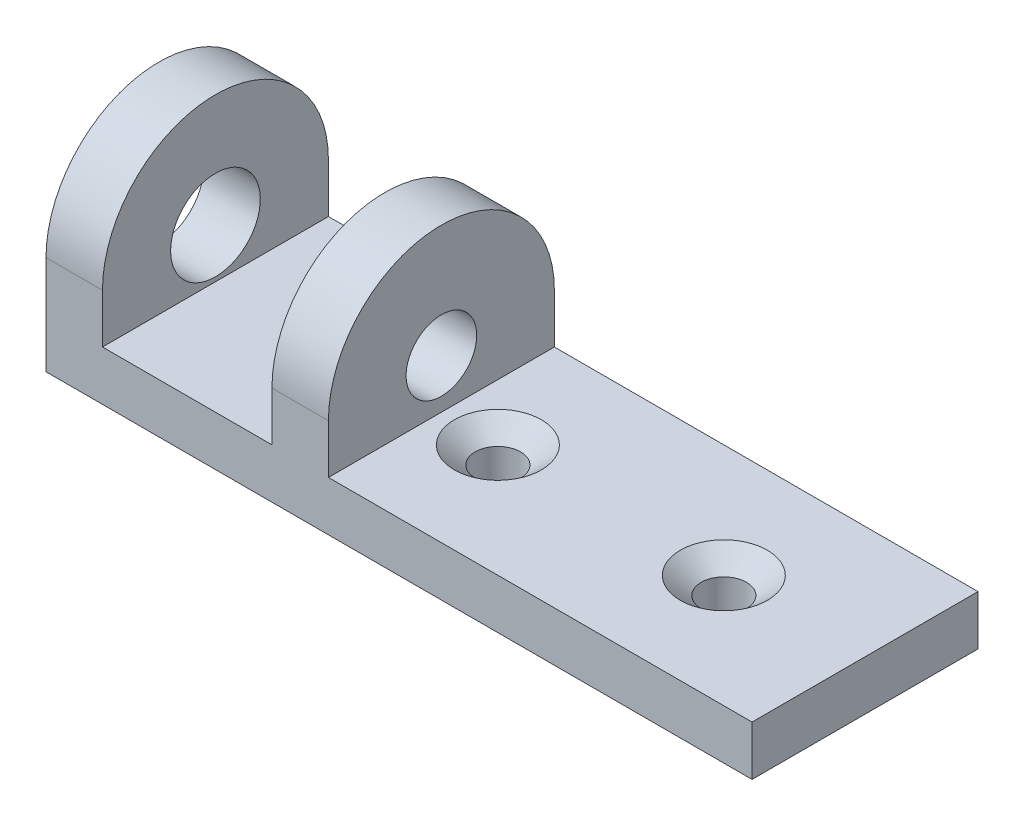
SolidWorks part; units mm, degrees
material "6061 Alloy"
ref_plane "Front" through (0, 0, 0) normal (0, 0, 1) x (1, 0, 0)
ref_plane "Top" through (0, 0, 0) normal (0, 1, 0) x (1, 0, 0)
ref_plane "Right" through (0, 0, 0) normal (1, 0, 0) x (0, 0, -1)
sketch "Sketch1" plane through (0, 0, 0) normal (1, 0, 0) x (0, 0, -1)
  line L0 (-12.7, 0) -> (-12.7, -11.1125)
  line L1 (-12.7, -11.1125) -> (12.7, -11.1125)
  line L2 (12.7, -11.1125) -> (12.7, 0)
  circle A0 centre (0, 0) radius 1.5875
  arc A1 (-12.7, 0) -> (12.7, 0) centre (0, 0) cw
  dimension "D1" = 3.175
  dimension "D2" = 25.4
  dimension "D3" = 11.1125
extrude "Boss-Extrude1" add sketch "Sketch1" along normal blind 79.375
sketch "Sketch2" plane through (0, 0, 12.7) normal (0, 0, 1) x (1, 0, 0)
  line L0 (79.375, 12.7) -> (0, 12.7) construction
  line L1 (6.35, 12.7) -> (25.4, 12.7)
  line L2 (6.35, 12.7) -> (6.35, -5.5245)
  line L3 (6.35, -5.5245) -> (25.4, -5.5245)
  line L4 (25.4, 12.7) -> (25.4, -5.5245)
  line L5 (79.375, 0) -> (79.375, -11.1125) construction
  line L6 (31.75, 12.7) -> (79.375, 12.7)
  line L7 (31.75, 12.7) -> (31.75, -5.5245)
  line L8 (31.75, -5.5245) -> (79.375, -5.5245)
  line L9 (79.375, 12.7) -> (79.375, -5.5245)
  line L10 (0, 12.7) -> (0, 0) construction
  line L11 (79.375, -11.1125) -> (0, -11.1125) construction
  dimension "D1" = 6.35
  dimension "D2" = 5.588
  dimension "D3" = 25.4
  dimension "D4" = 6.35
  dimension "D5" = 5.588
extrude "Cut-Extrude1" cut sketch "Sketch2" against normal through all
hole_wizard "CSK for #10 Flat Head Machine Screw (100)1" positions "Sketch5" profile "Sketch6" countersink size "#10" standard "ANSI Inch" end condition through all
sketch "Sketch5" plane through (0, -5.5245, 0) normal (0, 1, 0) x (1, 0, 0)
  line L0 (79.375, 0) -> (0, 0) construction
  line L1 (79.375, 12.7) -> (79.375, -12.7) construction
  point P8 (63.5, 0)
  point P10 (38.1, 0)
  dimension "D2" = 15.875
  dimension "D3" = 25.4
sketch "Sketch6" plane through (38.1, -5.5245, 0) normal (1, 0, 0) x (0, 0, 1)
  line L0 (0, 0) -> (0, 5.588)
  line L1 (0, 5.588) -> (2.5527, 5.588)
  line L2 (2.5527, 5.588) -> (2.5527, 1.9608)
  line L3 (2.5527, 1.9608) -> (4.8895, 0)
  line L5 (4.8895, 0) -> (0, 0)
  line L6 (-2.5527, 1.9608) -> (-4.8895, 0) construction
  line L11 (0, -6.35) -> (0, 107.95) construction
  dimension "Thru Hole Dia." = 5.1054
  dimension "Thru Hole Depth" = 5.588
  dimension "Near C'Sink Dia." = 9.779
  dimension "Near C'Sink Angle" = 100
hole_wizard "Tap Drill for 3/8-16 Tap1" positions "Sketch9" profile "Sketch10" hole size "3/8-16" standard "ANSI Inch"
sketch "Sketch9" plane through (31.75, 0, 0) normal (1, 0, 0) x (0, 0, -1)
  point P0 (0, 0)
sketch "Sketch10" plane through (31.75, 0, 0) normal (0, 1, 0) x (0, 0, -1)
  line L0 (0, 0) -> (0, 8.7337)
  line L1 (0, 8.7337) -> (3.9687, 6.349)
  line L2 (3.9687, 6.349) -> (3.9687, 0)
  line L5 (3.9687, 0) -> (0, 0)
  line L10 (0, 8.7337) -> (-3.9688, 6.349) construction
  line L11 (0, -6.35) -> (0, 107.95) construction
  dimension "Hole Dia." = 7.9375
  dimension "Hole Depth" = 6.349
  dimension "Drill Angle" = 118
hole_wizard "3/8 Clearance Hole1" positions "Sketch11" profile "Sketch12" hole size "3/8" standard "ANSI Inch"
sketch "Sketch11" plane through (0, 0, 0) normal (-1, 0, 0) x (0, 0, 1)
  point P0 (0, 0)
sketch "Sketch12" plane through (0, 0, 0) normal (0, 1, 0) x (0, 0, 1)
  line L0 (0, 0) -> (0, 9.3785)
  line L1 (0, 9.3785) -> (5.0419, 6.349)
  line L2 (5.0419, 6.349) -> (5.0419, 0)
  line L5 (5.0419, 0) -> (0, 0)
  line L10 (0, 9.3785) -> (-5.0419, 6.349) construction
  line L11 (0, -6.35) -> (0, 107.95) construction
  dimension "Hole Dia." = 10.0838
  dimension "Hole Depth" = 6.349
  dimension "Drill Angle" = 118
hole_wizard "CSK for #10 Flat Head Machine Screw (100)2" positions "Sketch13" profile "Sketch14" countersink size "#10" standard "ANSI Inch"
sketch "Sketch13" plane through (0, -5.5245, 0) normal (0, 1, 0) x (1, 0, 0)
  line L0 (0, 0) -> (25.4, 0) construction
  line L1 (25.4, 12.7) -> (25.4, -12.7) construction
  line L2 (3.175, 12.7) -> (3.175, -12.7) construction
  point P8 (6.35, 0)
  dimension "D1" = 3.175
sketch "Sketch14" plane through (6.35, -5.5245, 0) normal (1, 0, 0) x (0, 0, 1)
  line L0 (0, 0) -> (0, 5.588)
  line L1 (0, 5.588) -> (2.5527, 5.588)
  line L2 (2.5527, 5.588) -> (2.5527, 1.9608)
  line L3 (2.5527, 1.9608) -> (4.8895, 0)
  line L5 (4.8895, 0) -> (0, 0)
  line L6 (-2.5527, 1.9608) -> (-4.8895, 0) construction
  line L11 (0, -6.35) -> (0, 107.95) construction
  dimension "Thru Hole Dia." = 5.1054
  dimension "Thru Hole Depth" = 5.588
  dimension "Near C'Sink Dia." = 9.779
  dimension "Near C'Sink Angle" = 100
